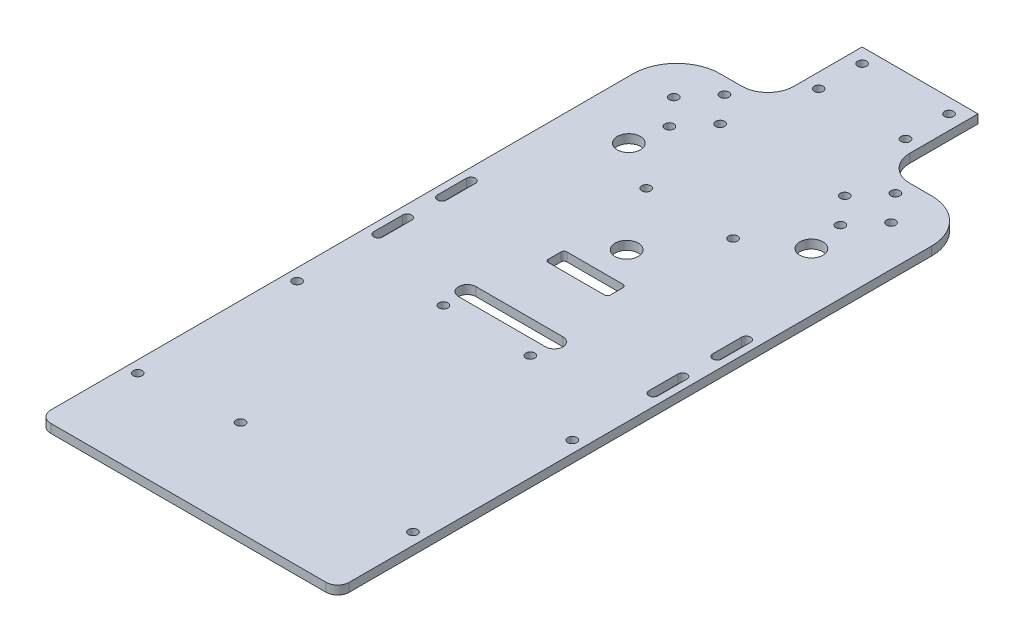
SolidWorks part; units mm, degrees
material "Hexcel AS4C (3000 丝)"
ref_plane "前视基准面" through (0, 0, 0) normal (0, 0, 1) x (1, 0, 0)
ref_plane "上视基准面" through (0, 0, 0) normal (0, 1, 0) x (1, 0, 0)
ref_plane "右视基准面" through (0, 0, 0) normal (1, 0, 0) x (0, 0, -1)
sketch "草图1" plane through (0, 0, 0) normal (0, 1, 0) x (1, 0, 0)
  line L1 (-100, 100) -> (100, 100)
  line L2 (-100, 100) -> (-100, -100)
  line L3 (-100, -100) -> (100, -100)
  line L4 (100, 100) -> (100, -100)
  line L5 (-100, 100) -> (100, -100) construction
  line L6 (-100, -100) -> (100, 100) construction
  point P0 (0, 0)
  dimension "D1" = 200
  dimension "D2" = 200
extrude "凸台-拉伸1" add sketch "草图1" along normal blind 3
sketch "草图2" plane through (0, 3, 0) normal (0, 1, 0) x (1, 0, 0)
  line L0 (0, 0) -> (0, 91) construction
  line L1 (-100, -100) -> (100, -100) construction
  line L2 (100, 100) -> (-100, 100) construction
  line L3 (-100, 0) -> (100, 0) construction
  line L5 (-100, 100) -> (-100, -100) construction
  line L6 (100, -100) -> (100, 100) construction
  line L7 (-29.5, 0) -> (29.5, 0) construction
  line L8 (-10, 100) -> (10, 100) construction
  line L9 (-10, 100) -> (-10, -100) construction
  line L10 (10, 100) -> (10, -100) construction
  line L11 (0, 0) -> (0, -29) construction
  line L13 (0, -29) -> (0, -32) construction
  circle A0 centre (-29.5, 0) radius 22.5 construction
  circle A1 centre (29.5, 0) radius 22.5 construction
  circle A2 centre (0, -29) radius 10.25 construction
  circle A3 centre (29.5, 0) radius 9.5 construction
  circle A4 centre (29.5, 0) radius 8 construction
  circle A5 centre (-29.5, 0) radius 8 construction
  circle A6 centre (-29.5, 0) radius 9.5 construction
  circle A7 centre (29.5, 9.5) radius 1.55
  circle A8 centre (21.5, 0) radius 1.55
  circle A9 centre (29.5, -9.5) radius 1.55
  circle A10 centre (37.5, 0) radius 1.55
  circle A11 centre (-29.5, -9.5) radius 1.55
  circle A12 centre (-37.5, 0) radius 1.55
  circle A13 centre (-21.5, 0) radius 1.55
  circle A14 centre (-29.5, 9.5) radius 1.55
  circle A15 centre (-15, -32) radius 1.55
  circle A16 centre (15, -32) radius 1.55
  point P16 (0, 0)
  dimension "D1" = 45
  dimension "D3" = 20.5
  dimension "D4" = 19
  dimension "D5" = 16
  dimension "D6" = 3.1
  dimension "D7" = 3.1
  dimension "D8" = 3.1
  dimension "D11" = 3.1
  dimension "D2" = 20
  dimension "D9" = 3
  dimension "D10" = 29
extrude "切除-拉伸2" cut sketch "草图2" against normal blind 10
sketch "草图4" plane through (0, 3, 0) normal (0, 1, 0) x (1, 0, 0)
  line L0 (0, 0) -> (0, 91)
  line L1 (100, 100) -> (-100, 100) construction
  line L2 (-10, 100) -> (10, 100)
  line L3 (-10, 100) -> (-10, -100) construction
  line L4 (-100, -100) -> (100, -100) construction
  line L5 (10, 100) -> (10, -100) construction
  line L6 (21.5, 0) -> (37.5, 0)
  line L7 (-29.5, 0) -> (0, 0)
  line L8 (0, -29) -> (0, 0)
  circle A0 centre (0, -29) radius 10.25
  circle A1 centre (29.5, 0) radius 8 construction
  circle A2 centre (29.5, 0) radius 9.5 construction
  circle A3 centre (29.5, 0) radius 22.5
  circle A4 centre (-29.5, 0) radius 9.5 construction
  circle A5 centre (-29.5, 0) radius 8 construction
  circle A6 centre (-29.5, 0) radius 22.5
  dimension "D1" = 20.5
  dimension "D2" = 19
  dimension "D3" = 16
  dimension "D4" = 45
sketch "草图5" plane through (0, 3, 0) normal (0, 1, 0) x (1, 0, 0)
  line L0 (44.5, -100) -> (51.5, -100)
  line L1 (-44.5, -100) -> (-51.5, -100)
  line L2 (-20, 24.995) -> (-20, 23.997)
  line L3 (-51.5, -100) -> (-51.5, -0.003)
  line L4 (-20, 47.5) -> (-20, 24.995)
  line L5 (51.5, -100) -> (51.5, -0.003)
  line L6 (-29, 14.997) -> (-36.5, 14.997)
  line L7 (-100, -100) -> (100, -100) construction
  line L8 (20, 47.5) -> (20, 24.995)
  line L9 (-100, -100) -> (-100, 100)
  line L10 (0, 0) -> (0, 91) construction
  line L11 (0, 47.5) -> (-20, 47.5)
  line L12 (44.5, -100) -> (-44.5, -100)
  line L13 (0, 47.5) -> (20, 47.5)
  line L14 (-100, 100) -> (100, 100)
  line L15 (100, 100) -> (100, -100)
  line L16 (20, 24.995) -> (20, 23.997)
  line L17 (29, 14.997) -> (36.5, 14.997)
  arc A0 (-29, 14.997) -> (-20, 23.997) centre (-29, 23.997) ccw
  arc A1 (29, 14.997) -> (20, 23.997) centre (29, 23.997) cw
  arc A2 (-51.5, -0.003) -> (-36.5, 14.997) centre (-36.5, -0.003) cw
  arc A3 (51.5, -0.003) -> (36.5, 14.997) centre (36.5, -0.003) ccw
  dimension "D1" = 9
  dimension "D2" = 15
  dimension "D5" = 9
  dimension "D6" = 15
  dimension "D3" = 7
  dimension "D4" = 7
extrude "切除-拉伸3" cut sketch "草图5" against normal blind 10
sketch "草图6" plane through (0, 0, 0) normal (0, -1, 0) x (1, 0, 0)
  line L0 (20, -47.5) -> (-20, -47.5) construction
  line L7 (-20, -47.5) -> (-20, -23.997) construction
  circle A1 centre (-15, -42.5) radius 1.55
  circle A2 centre (-15, -27.5) radius 1.55
  circle A3 centre (15, -27.5) radius 1.55
  circle A4 centre (15, -42.5) radius 1.55
  dimension "D1" = 3.1
  dimension "D2" = 5
  dimension "D3" = 5
  dimension "D4" = 30
extrude "φ3.1通孔1" cut sketch "草图6" against normal blind 10
sketch "草图7" plane through (0, 3, 0) normal (0, 1, 0) x (1, 0, 0)
  line L5 (-49.05, -70) -> (-49.05, -60)
  line L6 (-45.95, -70) -> (-45.95, -60)
  line L7 (-49.05, -65) -> (-45.95, -65) construction
  line L8 (-49.05, -92) -> (-49.05, -82)
  line L9 (-45.95, -92) -> (-45.95, -82)
  line L10 (49.05, -87) -> (45.95, -87) construction
  line L11 (-49.05, -87) -> (-45.95, -87) construction
  line L12 (49.05, -65) -> (45.95, -65) construction
  line L13 (45.95, -92) -> (45.95, -82)
  line L14 (49.05, -92) -> (49.05, -82)
  line L15 (45.95, -70) -> (45.95, -60)
  line L16 (49.05, -70) -> (49.05, -60)
  arc A0 (-45.95, -92) -> (-49.05, -92) centre (-47.5, -92) cw
  arc A1 (-45.95, -70) -> (-49.05, -70) centre (-47.5, -70) cw
  arc A2 (-45.95, -60) -> (-49.05, -60) centre (-47.5, -60) ccw
  arc A3 (45.95, -82) -> (49.05, -82) centre (47.5, -82) cw
  arc A4 (45.95, -60) -> (49.05, -60) centre (47.5, -60) cw
  arc A5 (-45.95, -82) -> (-49.05, -82) centre (-47.5, -82) ccw
  arc A6 (45.95, -70) -> (49.05, -70) centre (47.5, -70) ccw
  arc A7 (45.95, -92) -> (49.05, -92) centre (47.5, -92) ccw
  point P25 (-29.5, 0)
  dimension "D1" = 65
sketch "草图9" plane through (0, 3, 0) normal (0, 1, 0) x (1, 0, 0)
  circle A0 centre (0, -53.75) radius 4
  dimension "D1" = 8
extrude "舵机下圆柱孔" cut sketch "草图9" against normal through all
sketch "草图11" plane through (0, 0, 100) normal (0, 0, 1) x (1, 0, 0)
  line L0 (-44.5, 3) -> (-51.5, 3)
  line L1 (-44.5, 0) -> (44.5, 0)
  line L2 (-51.5, 3) -> (-51.5, 0)
  line L3 (44.5, 3) -> (-44.5, 3)
  line L4 (-51.5, 0) -> (-44.5, 0)
  line L5 (44.5, 3) -> (51.5, 3)
  line L6 (51.5, 3) -> (51.5, 0)
  line L7 (51.5, 0) -> (44.5, 0)
extrude "凸台-拉伸2" add sketch "草图11" along normal blind 30
sketch "草图10" plane through (0, 0, 0) normal (0, -1, 0) x (1, 0, 0)
  line L1 (0, 0) -> (0, 9.5) construction
  line L2 (-51.5, 130) -> (-51.5, 0.003) construction
  circle A0 centre (-31.5, 21.5) radius 4
  circle A1 centre (31.5, 21.5) radius 4
  dimension "D2" = 8
  dimension "D3" = 20
extrude "2006电机穿线孔" cut sketch "草图10" against normal up to next
sketch "草图12" plane through (0, 3, 0) normal (0, 1, 0) x (1, 0, 0)
  line L2 (-9.7, -64.7) -> (9.7, -64.7)
  line L3 (10.7, -65.7) -> (10.7, -70.08)
  line L4 (9.7, -71.08) -> (-9.7, -71.08)
  line L5 (-10.7, -70.08) -> (-10.7, -65.7)
  arc A0 (9.7, -71.08) -> (10.7, -70.08) centre (9.7, -70.08) ccw
  arc A1 (10.7, -65.7) -> (9.7, -64.7) centre (9.7, -65.7) ccw
  arc A2 (-9.7, -71.08) -> (-10.7, -70.08) centre (-9.7, -70.08) cw
  arc A3 (-10.7, -65.7) -> (-9.7, -64.7) centre (-9.7, -65.7) cw
  point P10 (10.7, -64.7)
  point P13 (-10.7, -71.08)
  point P16 (-10.7, -64.7)
  dimension "D5" = 1
  dimension "D1" = 21.4
  dimension "D2" = 6.38
  dimension "D3" = 10.95
  dimension "D4" = 10.7
extrude "舵机穿线孔" cut sketch "草图12" against normal up to next
extrude "切除-拉伸4" cut sketch "草图7" against normal blind 10
sketch "草图13" plane through (0, 0, 130) normal (0, 0, 1) x (1, 0, 0)
  line L0 (-51.5, 3) -> (-51.5, 0)
  line L1 (-51.5, 0) -> (51.5, 0)
  line L2 (51.5, 0) -> (51.5, 3)
  line L3 (51.5, 3) -> (-51.5, 3)
extrude "凸台-拉伸3" add sketch "草图13" along normal blind 75
sketch "草图14" plane through (0, 3, 0) normal (0, 1, 0) x (1, 0, 0)
  line L0 (0, -53.75) -> (0, -92.498) construction
  line L1 (-15, -90.75) -> (15, -90.75)
  line L2 (15, -96.75) -> (-15, -96.75)
  arc A0 (-15, -90.75) -> (-15, -96.75) centre (-15, -93.75) ccw
  arc A1 (15, -90.75) -> (15, -96.75) centre (15, -93.75) cw
  dimension "D3" = 3
  dimension "D1" = 40
  dimension "D2" = 30
extrude "主控板穿线孔" cut sketch "草图14" against normal blind 10
sketch "草图15" plane through (0, 3, 0) normal (0, 1, 0) x (1, 0, 0)
  line L0 (51.5, -205) -> (-51.5, -205) construction
  line L1 (0, -125.3392) -> (0, -153.9249) construction
  line L2 (-51.5, -205) -> (-51.5, -0.003) construction
  circle A0 centre (-47.5, -175) radius 1.55
  circle A1 centre (-47.5, -120) radius 1.55
  circle A2 centre (47.5, -120) radius 1.55
  circle A3 centre (47.5, -175) radius 1.55
  dimension "D1" = 3.1
  dimension "D3" = 3.1
  dimension "D2" = 30
  dimension "D4" = 55
  dimension "D5" = 4
  dimension "D6" = 4
hole_wizard "Ø3.1 (3.1) 直径孔1" positions "3D草图1" profile "草图16" hole size "Ø3.1" standard "GB" end condition through all
sketch3d "3D草图1"
  point P0 (-47.5, 3, 120)
  point P3 (47.5, 3, 120)
  point P6 (-47.5, 3, 175)
  point P9 (47.5, 3, 175)
sketch "草图16" plane through (-47.5, 3, 120) normal (1, 0, 0) x (0, 0, 1)
  line L0 (0, 0) -> (0, 3)
  line L1 (0, 3) -> (1.55, 3)
  line L2 (1.55, 3) -> (1.55, 0)
  line L5 (1.55, 0) -> (0, 0)
  line L11 (0, -6.35) -> (0, 107.95) construction
  dimension "通孔孔直径" = 3.1
  dimension "通孔孔深度" = 3
fillet "圆角1" radius 4 2 edges at (51.5, 1.5, 205) (-51.5, 1.5, 205)
sketch "草图17" plane through (0, 3, 0) normal (0, 1, 0) x (1, 0, 0)
  line L0 (0, -53.75) -> (0, -158.5795) construction
  circle A0 centre (-15, -102) radius 1.55
  arc A1 (-15, -90.75) -> (-15, -96.75) centre (-15, -93.75) ccw construction
  circle A2 centre (-15, -172) radius 1.55
  circle A3 centre (15, -102) radius 1.55
  dimension "D1" = 3.1
  dimension "D2" = 8.25
  dimension "D3" = 15
  dimension "D4" = 3.1
  dimension "D5" = 70
hole_wizard "Ø3.1 (3.1) 直径孔2" positions "3D草图2" profile "草图18" hole size "Ø3.1" standard "GB" end condition up to next
sketch3d "3D草图2"
  point P0 (-15, 3, 102)
  point P3 (15, 3, 102)
  point P6 (-15, 3, 172)
sketch "草图18" plane through (-15, 3, 102) normal (1, 0, 0) x (0, 0, 1)
  line L0 (0, 0) -> (0, 3)
  line L1 (0, 3) -> (1.55, 3)
  line L2 (1.55, 3) -> (1.55, 0)
  line L5 (1.55, 0) -> (0, 0)
  line L11 (0, -6.35) -> (0, 107.95) construction
  dimension "通孔孔直径" = 3.1
  dimension "通孔孔深度" = 3
